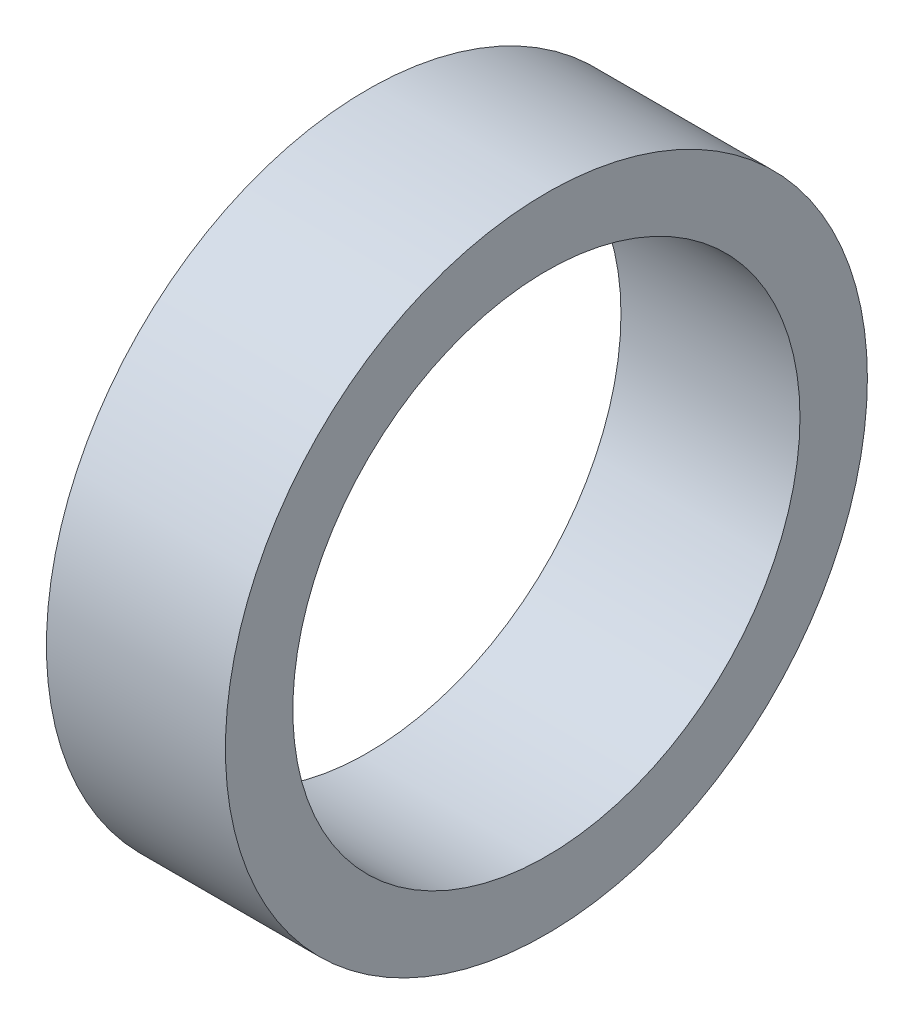
SolidWorks part; units mm, degrees
ref_plane "Front Plane" through (0, 0, 0) normal (0, 0, 1) x (1, 0, 0)
ref_plane "Top Plane" through (0, 0, 0) normal (0, 1, 0) x (1, 0, 0)
ref_plane "Right Plane" through (0, 0, 0) normal (1, 0, 0) x (0, 0, -1)
sketch "Sketch1" plane through (0, 0, 0) normal (1, 0, 0) x (0, 0, -1)
  circle A0 centre (0, 0) radius 42.5
  circle A2 centre (0, 48) radius 2.8
  circle A3 centre (48, 0) radius 2.8
  circle A4 centre (0, -48) radius 2.8
  circle A5 centre (-48, 0) radius 2.8
  circle A7 centre (0, 0) radius 53.8
  point P15 (0, 0)
  dimension "D1" = 4
extrude "Boss-Extrude1" add sketch "Sketch1" along normal blind 20
sketch "Sketch3" plane through (20, 0, 0) normal (1, 0, 0) x (0, 0, -1)
  circle A0 centre (0, 0) radius 53.8
  circle A1 centre (0, 0) radius 42.5
extrude "Boss-Extrude2" add sketch "Sketch3" along normal blind 10
